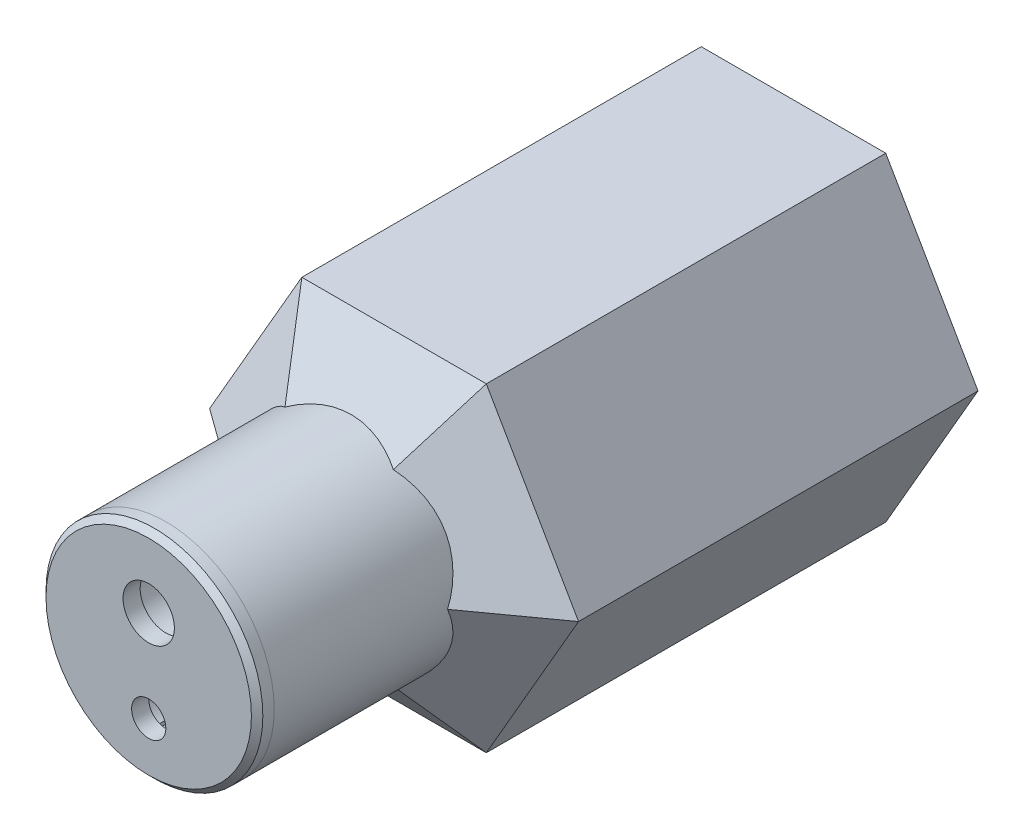
SolidWorks part; units mm, degrees
ref_plane "Přední rovina" through (0, 0, 0) normal (0, 0, 1) x (1, 0, 0)
ref_plane "Horní rovina" through (0, 0, 0) normal (0, 1, 0) x (1, 0, 0)
ref_plane "Pravá rovina" through (0, 0, 0) normal (1, 0, 0) x (0, 0, -1)
sketch "Skica1" plane through (0, 0, 0) normal (0, 0, 1) x (1, 0, 0)
  line L0 (-1000, 0) -> (49000, 0) construction
  line L1 (12.7017, 2) -> (6.9282, 12)
  line L2 (6.9282, 12) -> (-6.9282, 12)
  line L3 (-6.9282, 12) -> (-12.7017, 2)
  line L4 (-11.6625, -3.8) -> (-6.9282, -12)
  line L5 (-6.9282, -12) -> (6.9282, -12)
  line L6 (6.9282, -12) -> (11.6625, -3.8)
  line L7 (0, -1000) -> (0, 49000) construction
  line L8 (-16.1658, 0) -> (-8.0829, -14)
  line L9 (-8.0829, -14) -> (8.0829, -14)
  line L10 (8.0829, -14) -> (16.1658, 0)
  line L11 (16.1658, 0) -> (8.0829, 14)
  line L12 (8.0829, 14) -> (-8.0829, 14)
  line L13 (-8.0829, 14) -> (-16.1658, 0)
  line L14 (-9.3564, 0) -> (-10.2064, 0)
  line L15 (-9.3564, 0) -> (-9.3564, 2)
  line L16 (-9.3564, 2) -> (-12.7017, 2)
  line L17 (8.7064, -3.8) -> (11.6625, -3.8)
  line L18 (-10.2064, 0) -> (-10.2064, -1.8)
  line L19 (-10.2064, -1.8) -> (-8.7064, -1.8)
  line L20 (-8.7064, -1.8) -> (-8.7064, -3.8)
  line L21 (-8.7064, -3.8) -> (-11.6625, -3.8)
  line L22 (8.7064, -1.8) -> (8.7064, -3.8)
  line L23 (10.2064, -1.8) -> (8.7064, -1.8)
  line L24 (10.2064, 0) -> (10.2064, -1.8)
  line L25 (9.3564, 0) -> (10.2064, 0)
  line L26 (9.3564, 0) -> (9.3564, 2)
  line L27 (9.3564, 2) -> (12.7017, 2)
  line L28 (-6.9282, 12) -> (-13.8564, 0) construction
  line L29 (-13.8564, 0) -> (-6.9282, -12) construction
  line L30 (6.9282, -12) -> (13.8564, 0) construction
  line L31 (13.8564, 0) -> (6.9282, 12) construction
  circle A0 centre (0, 0) radius 12 construction
  dimension "D1" = 24
  dimension "D4" = 2
  dimension "D5" = 0.85
  dimension "D6" = 1.8
  dimension "D7" = 9.3564
  dimension "D8" = 1.5
  dimension "D9" = 2
  dimension "D2" = 2
extrude "Přidat vysunutím1" add sketch "Skica1" along normal blind 35
ref_plane "Rovina1" through (0, 0, 40) normal (0, 0, 1) x (1, 0, 0)
sketch "Skica5" plane through (0, 0, 40) normal (0, 0, 1) x (1, 0, 0)
  line L36 (9.2376, 0) -> (4.6188, 8)
  line L37 (-4.6188, 8) -> (-9.2376, 0)
  line L38 (4.6188, 8) -> (-4.6188, 8)
  line L39 (9.2376, 0) -> (4.6188, 8)
  line L40 (-4.6188, 8) -> (-9.2376, 0)
  line L41 (4.6188, 8) -> (-4.6188, 8)
  line L48 (4.6188, -8) -> (8.1984, -1.8)
  line L49 (-4.6188, -8) -> (4.6188, -8)
  line L50 (-8.1984, -1.8) -> (-4.6188, -8)
  line L51 (4.6188, -8) -> (9.2376, 0)
  line L52 (-4.6188, -8) -> (4.6188, -8)
  line L53 (-9.2376, 0) -> (-4.6188, -8)
  dimension "D1" = 4
  dimension "D2" = 4
ref_plane "Rovina3" through (0, 22.9508, 27.541) normal (0, -0.6402, -0.7682) x (-1, 0, 0)
sketch "Skica6" plane through (0, 22.9508, 27.541) normal (0, -0.6402, -0.7682) x (-1, 0, 0)
  line L3 (-4.6188, -19.4616) -> (4.6188, -19.4616)
  line L4 (8.0829, -11.6514) -> (4.6188, -19.4616)
  line L5 (-4.6188, -19.4616) -> (-8.0829, -11.6514)
  line L6 (-8.0829, -11.6514) -> (8.0829, -11.6514)
extrude "Přidat vysunutím2" add sketch "Skica6" along normal blind 2 separate body
sketch "Skica9" plane through (0, 0, 40) normal (0, 0, 1) x (1, 0, 0)
  circle A0 centre (0, 0) radius 9.5
  circle A1 centre (0, 0) radius 7.5
  dimension "D1" = 19
  dimension "D2" = 15
extrude "Přidat vysunutím3" add sketch "Skica9" along normal blind 15
pattern_circular "Kruhové pole1" count 6 over 360 about axis through (0, 0, 0) along (0, 0, 1) of bodies 102
sketch "Skica14" plane through (0, 0, 35) normal (0, 0, 1) x (1, 0, 0)
  line L0 (-9.3564, 2) -> (-12.7017, 2)
  line L1 (-9.3564, 2) -> (-9.3564, 0)
  line L2 (-9.3564, 0) -> (-10.2064, 0)
  line L3 (-10.2064, 0) -> (-10.2064, -1.8)
  line L4 (-10.2064, -1.8) -> (-8.7064, -1.8)
  line L5 (-8.7064, -1.8) -> (-8.7064, -3.8)
  line L6 (-8.7064, -3.8) -> (-11.6625, -3.8)
  line L7 (-11.6625, -3.8) -> (-12.7017, 2)
  line L8 (11.6625, -3.8) -> (8.7064, -3.8)
  line L9 (8.7064, -3.8) -> (8.7064, -1.8)
  line L10 (8.7064, -1.8) -> (10.2064, -1.8)
  line L11 (10.2064, -1.8) -> (10.2064, 0)
  line L12 (10.2064, 0) -> (9.3564, 0)
  line L13 (9.3564, 0) -> (9.3564, 2)
  line L14 (9.3564, 2) -> (12.7017, 2)
  line L15 (12.7017, 2) -> (11.6625, -3.8)
sketch "Skica10" plane through (0, 0, 40) normal (0, 0, -1) x (-1, 0, 0)
  circle A0 centre (0, 0) radius 9.5
  circle A1 centre (0, 0) radius 7.5
  dimension "D1" = 19
  dimension "D2" = 15
extrude "Přidat vysunutím4" add sketch "Skica10" along normal blind 1.5
sketch "Skica11" plane through (0, 0, 38.5) normal (0, 0, -1) x (-1, 0, 0)
  circle A0 centre (0, 0) radius 7.5
  dimension "D1" = 15
extrude "Odebrat vysunutím1" cut sketch "Skica11" along normal blind 10 and the other way through all
sketch "Skica12" plane through (0, 0, 38.5) normal (0, 0, -1) x (-1, 0, 0)
  line L0 (-1000, 0) -> (49000, 0) construction
  line L1 (-5.2, -1.8) -> (-5.2, 0)
  line L2 (7.5, 1) -> (7.5, -2.8)
  line L4 (5.2, -1.8) -> (4, -1.8)
  line L5 (5.2, 0) -> (4, 0)
  line L6 (4, -1.8) -> (4, -2.8)
  line L7 (4, -2.8) -> (7.5, -2.8)
  line L9 (4, 0) -> (4, 1)
  line L10 (4, 1) -> (7.5, 1)
  line L12 (0, -1000) -> (0, 49000) construction
  line L21 (-4, 1) -> (-7.5, 1)
  line L22 (5.2, -1.8) -> (5.2, 0)
  line L23 (-4, 0) -> (-4, 1)
  line L24 (-4, -2.8) -> (-7.5, -2.8)
  line L25 (-4, -1.8) -> (-4, -2.8)
  line L26 (-5.2, 0) -> (-4, 0)
  line L27 (-5.2, -1.8) -> (-4, -1.8)
  line L28 (-7.5, 1) -> (-7.5, -2.8)
  dimension "D1" = 3.8
  dimension "D2" = 3.5
  dimension "D3" = 1
  dimension "D4" = 1.8
  dimension "D5" = 1.2
  dimension "D6" = 1
  dimension "D7" = 7.5
  dimension "D8" = 1.2
  dimension "D9" = 1
extrude "Přidat vysunutím5" add sketch "Skica12" against normal blind 6.7
chamfer "Zkosení2" distance 3 angle 45 2 edges at (-4, -2.3, 38.5) (4, 0.5, 38.5)
extrude "Přidat vysunutím6" add sketch "Skica14" along normal up to next
sketch "Skica16" plane through (0, 0, 45.2) normal (0, 0, 1) x (1, 0, 0)
  line L7 (-4, -2.8) -> (-4, 1)
  line L14 (-4, 1) -> (-7.433, 1)
  line L15 (-6.9577, -2.8) -> (-4, -2.8)
  line L16 (-4, -2.8) -> (-4, -1.8)
  line L17 (-4, -1.8) -> (-5.2, -1.8)
  line L18 (-5.2, -1.8) -> (-5.2, 0)
  line L19 (-5.2, 0) -> (-4, 0)
  line L20 (-4, 0) -> (-4, 1)
  line L21 (-4, 1) -> (-7.433, 1)
  line L22 (-6.9577, -2.8) -> (-4, -2.8)
  line L29 (4, -2.8) -> (4, 1)
  line L36 (7.433, 1) -> (4, 1)
  line L37 (4, 1) -> (4, 0)
  line L38 (4, 0) -> (5.2, 0)
  line L39 (5.2, 0) -> (5.2, -1.8)
  line L40 (5.2, -1.8) -> (4, -1.8)
  line L41 (4, -1.8) -> (4, -2.8)
  line L42 (4, -2.8) -> (6.9577, -2.8)
  line L43 (7.433, 1) -> (4, 1)
  line L49 (4, -2.8) -> (6.9577, -2.8)
  arc A2 (-7.433, 1) -> (-6.9577, -2.8) centre (0, 0) ccw
  arc A3 (-7.433, 1) -> (-6.9577, -2.8) centre (0, 0) ccw
  arc A5 (6.9577, -2.8) -> (7.433, 1) centre (0, 0) ccw
  arc A6 (6.9577, -2.8) -> (7.433, 1) centre (0, 0) ccw
  dimension "D1" = 0
  dimension "D2" = 0
extrude "Přidat vysunutím7" add sketch "Skica16" along normal blind 1
sketch "Skica17" plane through (0, 0, 0) normal (0, 1, 0) x (1, 0, 0)
  line L0 (-4, -45.2) -> (4, -45.2) construction
  line L1 (-4, -45.7) -> (4, -45.7)
  line L2 (-4, -46.2) -> (-4, -41.5) construction
  line L3 (-4, -46.2) -> (-4, -45.7)
  line L4 (4, -46.2) -> (4, -45.7)
  line L5 (-4, -46.2) -> (-7.5, -46.2)
  line L6 (-7.5, -46.2) -> (-6.9577, -46.2) construction
  line L7 (-7.5, -46.2) -> (-7.5, -55)
  line L8 (-7.5, -55) -> (7.5, -55) construction
  line L9 (-9.5, -55) -> (9.5, -55) construction
  line L10 (-7.5, -55) -> (7.5, -55)
  line L11 (7.5, -55) -> (7.5, -46.2)
  line L12 (6.9577, -46.2) -> (7.5, -46.2) construction
  line L13 (7.5, -46.2) -> (4, -46.2)
  dimension "D1" = 0.5
  dimension "D2" = 15
  dimension "D3" = 3.5
extrude "Přidat vysunutím8" add sketch "Skica17" against normal blind 1.8
sketch "Skica18" plane through (0, 0, 55) normal (0, 0, 1) x (1, 0, 0)
  line L0 (-7.5, 0) -> (7.5, 0) construction
  circle A0 centre (0, 0) radius 9.5
extrude "Přidat vysunutím9" add sketch "Skica18" along normal blind 1.5 separate body
sketch "Skica19" plane through (0, 0, 56.5) normal (0, 0, 1) x (1, 0, 0)
  circle A0 centre (0, 3.3) radius 2.25
  circle A1 centre (0, -4.7) radius 1.5
  dimension "D1" = 4.5
  dimension "D2" = 3
  dimension "D3" = 3.3
  dimension "D4" = 4.7
extrude "Odebrat vysunutím3" cut sketch "Skica19" against normal up to next (1.5 mm away)
sketch "Skica20" plane through (0, 0, 55) normal (0, 0, -1) x (-1, 0, 0)
  line L4 (-7.2553, -1.9) -> (-6.2161, -1.9)
  line L5 (6.2161, -1.9) -> (7.2553, -1.9)
  line L6 (-7.4993, 0.1) -> (-6.4992, 0.1)
  line L7 (6.4992, 0.1) -> (7.4993, 0.1)
  line L10 (-1.65, -1.9) -> (-1.4671, -1.9)
  line L11 (-1.4671, -7.3551) -> (-1.4671, -7.0259)
  line L12 (1.4671, -7.3551) -> (1.4671, -7.0259)
  line L15 (1.4671, -1.9) -> (1.65, -1.9)
  line L16 (-1.4671, -2.3741) -> (-1.4671, -1.9)
  line L17 (1.4671, -2.3741) -> (1.4671, -1.9)
  line L18 (-0.5679, 0.1) -> (0.5679, 0.1)
  arc A5 (-7.2553, -1.9) -> (-1.4671, -7.3551) centre (0, 0) ccw
  arc A6 (-6.2161, -1.9) -> (-3.0855, -5.721) centre (0, 0) ccw
  arc A7 (6.4992, 0.1) -> (0.7955, 6.4511) centre (0, 0) ccw
  arc A8 (7.4993, 0.1) -> (-7.4993, 0.1) centre (0, 0) ccw
  arc A9 (3.0855, -5.721) -> (6.2161, -1.9) centre (0, 0) ccw
  arc A12 (-1.4671, -2.3741) -> (-1.4671, -7.0259) centre (0, -4.7) ccw
  arc A13 (3.0855, -5.721) -> (1.65, -1.9) centre (0, -4.7) ccw
  arc A14 (-1.65, -1.9) -> (-3.0855, -5.721) centre (0, -4.7) ccw
  arc A15 (1.4671, -7.3551) -> (7.2553, -1.9) centre (0, 0) ccw
  arc A16 (1.4671, -7.0259) -> (1.4671, -2.3741) centre (0, -4.7) ccw
  circle A17 centre (0, 3.3) radius 2.75
  arc A18 (-0.7955, 6.4511) -> (-0.5679, 0.1) centre (0, 3.3) ccw
  arc A19 (-0.7955, 6.4511) -> (-6.4992, 0.1) centre (0, 0) ccw
  arc A20 (0.5679, 0.1) -> (0.7955, 6.4511) centre (0, 3.3) ccw
  dimension "D2" = 13
  dimension "D1" = 15
  dimension "D4" = 6.5
  dimension "D5" = 6.5
  dimension "D7" = 5.5
  dimension "D3" = 5.5
  dimension "D9" = 1.9
  dimension "D10" = 2
  dimension "D11" = 6.4992
extrude "Přidat vysunutím11" add sketch "Skica20" along normal blind 4 separate body
chamfer "Zkosení3" distance 0.5 angle 45 1 edges at (9.5, 0, 56.5)
